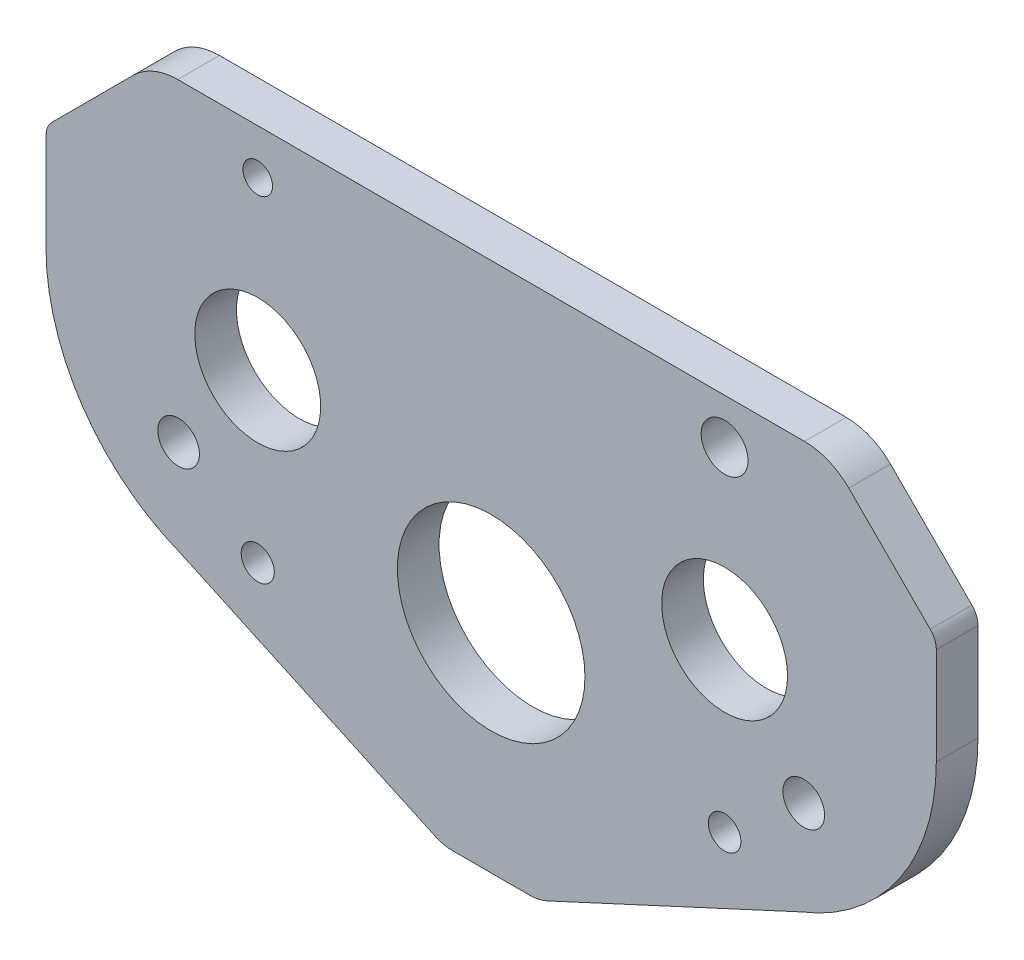
SolidWorks part; units mm, degrees
ref_plane "Front Plane" through (0, 0, 0) normal (0, 0, 1) x (1, 0, 0)
ref_plane "Top Plane" through (0, 0, 0) normal (0, 1, 0) x (1, 0, 0)
ref_plane "Right Plane" through (0, 0, 0) normal (1, 0, 0) x (0, 0, -1)
sketch "Sketch1" plane through (0, 0, 0) normal (0, 0, 1) x (1, 0, 0)
  line L0 (-35.5639, 47.7989) -> (35.5639, 47.7989)
  line L6 (-67.8219, 15.5409) -> (-67.8219, 31.6699)
  line L7 (-51.6929, 47.7989) -> (-35.5639, 47.7989)
  line L8 (35.5639, 47.7989) -> (51.6929, 47.7989)
  line L9 (67.8219, 31.6699) -> (67.8219, 15.5409)
  line L10 (-35.5639, -9.8591) -> (-35.5639, 40.9409) construction
  line L11 (-47.3214, -14.4981) -> (-7.2646, -33.02)
  line L12 (47.3214, -14.4981) -> (7.2646, -33.02)
  line L13 (-90.8786, 25.4) -> (90.8786, 25.4) construction
  line L14 (-90.8786, 25.4) -> (-90.8786, -25.4) construction
  line L15 (-90.8786, -25.4) -> (90.8786, -25.4) construction
  line L16 (90.8786, 25.4) -> (90.8786, -25.4) construction
  line L17 (-90.8786, 25.4) -> (90.8786, -25.4) construction
  line L18 (-90.8786, -25.4) -> (90.8786, 25.4) construction
  line L19 (-7.2646, -33.02) -> (7.2646, -33.02)
  line L20 (-67.8219, 31.6699) -> (-51.6929, 47.7989)
  line L21 (51.6929, 47.7989) -> (67.8219, 31.6699)
  circle A0 centre (0, 0) radius 6.35 construction
  circle A1 centre (0, 0) radius 14.2875
  circle A2 centre (35.5639, 15.5409) radius 9.5885
  circle A3 centre (-35.5639, 15.5409) radius 9.5885
  circle A4 centre (-35.5639, 15.5409) radius 32.258 construction
  circle A5 centre (35.5639, 15.5409) radius 32.258 construction
  circle A6 centre (0, 0) radius 33.02 construction
  circle A7 centre (0, 0) radius 50.8 construction
  circle A8 centre (-47.625, 0) radius 3.175
  circle A9 centre (47.625, 0) radius 3.175
  circle A10 centre (-35.5639, 40.9409) radius 2.2573
  circle A11 centre (-35.5639, -9.8591) radius 2.522
  circle A12 centre (35.5639, -9.8591) radius 2.4815
  circle A13 centre (35.5639, 40.9409) radius 3.5671
  arc A14 (-47.3214, -14.4981) -> (-67.8219, 15.5409) centre (-35.5639, 15.5409) cw
  arc A15 (47.3214, -14.4981) -> (67.8219, 15.5409) centre (35.5639, 15.5409) ccw
  dimension "D1" = 28.575
  dimension "D2" = 12.7
  dimension "D3" = 19.177
  dimension "D6" = 64.516
  dimension "D7" = 66.04
  dimension "D9" = 101.6
  dimension "D10" = 6.35
  dimension "D4" = 38.8112
  dimension "D5" = 38.8112
  dimension "D8" = 50.8
  dimension "D11" = 47.625
  dimension "D12" = 47.625
  dimension "D13" = 50.8
extrude "Boss-Extrude1" add sketch "Sketch1" along normal mid plane 6.35
fillet "Fillet1" radius 9.525 2 edges at (51.6929, 47.7989, 0) (-51.6929, 47.7989, 0)
fillet "Fillet2" radius 3.175 2 edges at (67.8219, 31.6699, 0) (-67.8219, 31.6699, 0)
fillet "Fillet3" radius 6.35 2 edges at (7.2646, -33.02, 0) (-7.2646, -33.02, 0)
